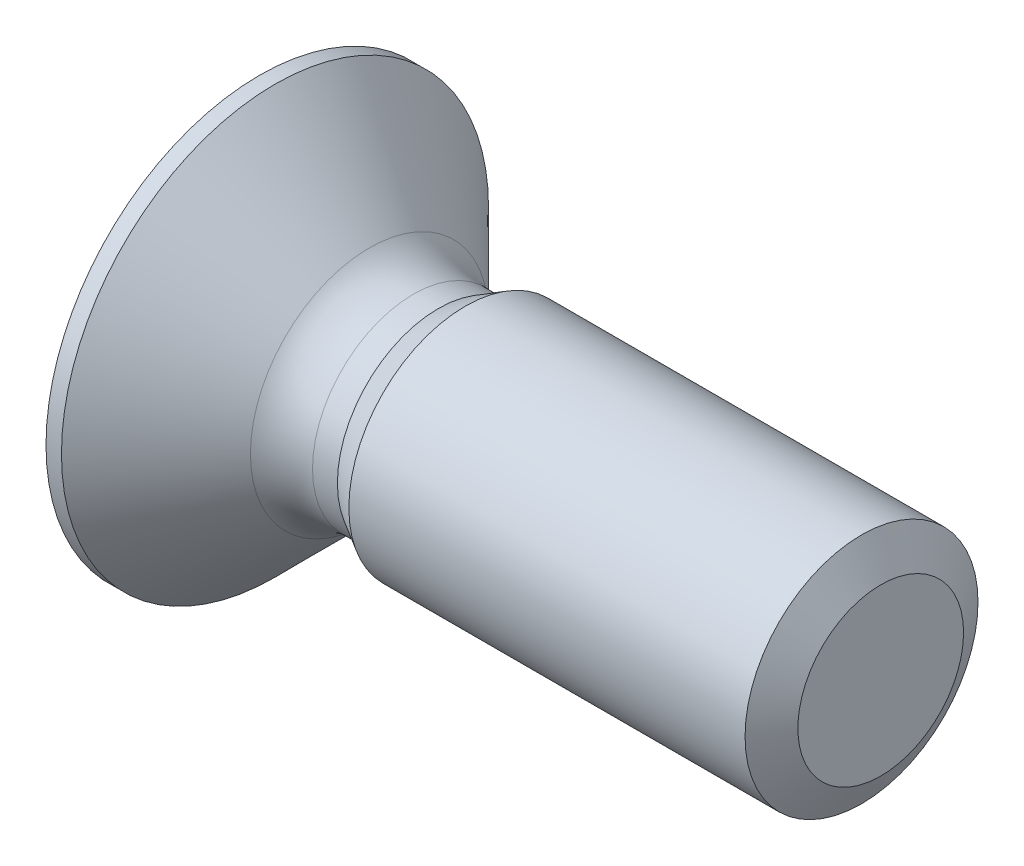
SolidWorks part; units mm, degrees
revolve "基体-旋转" add sketch "草图1" angle 360 about L0
sketch "草图1" plane through (0, 0, 0) normal (0, 0, 1) x (1, 0, 0)
  line L0 (0, 0) -> (4.4175, 0) construction
  line L1 (0, 0) -> (0, 2.75)
  line L2 (0, 2.75) -> (0.199, 2.75)
  line L3 (0.199, 2.75) -> (1.4157, 1.5333)
  line L4 (1.9814, 1.299) -> (2.3019, 1.299)
  line L5 (2.3019, 1.299) -> (2.65, 1.5)
  line L6 (2.65, 1.5) -> (8, 1.5)
  line L7 (8, 1.5) -> (8, 0)
  line L8 (0, 0) -> (8, 0)
  arc A0 (1.9814, 1.299) -> (1.4157, 1.5333) centre (1.9814, 2.099) cw
  point P12 (1.65, 1.299)
  dimension "D2" = 0.8
  dimension "D1" = 2.598
  dimension "d" = 3
  dimension "dk" = 5.5
  dimension "k" = 1.65
  dimension "D5" = 45
  dimension "a" = 1
  dimension "l" = 8
  dimension "D8" = 30
cosmetic thread "装饰螺纹线2" parameters "D1"=5.35, "D2"=2.5
material "AISI 304"
ref_plane "前视" through (0, 0, 0) normal (0, 0, 1) x (1, 0, 0)
ref_plane "上视" through (0, 0, 0) normal (0, 1, 0) x (1, 0, 0)
ref_plane "右视" through (0, 0, 0) normal (1, 0, 0) x (0, 0, -1)
sketch "尺寸草图" plane through (0, 0, 0) normal (0, 0, 1) x (1, 0, 0)
  line L0 (0, 0) -> (8, 0)
  point P3 (1.65, 0)
  point P4 (1, 0)
  point P5 (3, 0)
  point P6 (5.5, 0)
  point P7 (4.8, 0)
  point P8 (3.5943, 0)
  point P9 (7.2, 0)
  point P10 (5.9, 0)
  point P11 (7.5, 0)
  dimension "d" = 3
  dimension "dk" = 5.5
  dimension "k" = 1.65
  dimension "a" = 1
  dimension "l" = 8
  dimension "r" = 0.8
  dimension "m" = 3.2
  dimension "h" = 2.1
  dimension "p" = 0.5
sketch "草图2" plane through (0, 0, 0) normal (0, 0, 1) x (1, 0, 0)
  line L0 (7.7527, 1.5) -> (8.2527, 1.5)
  line L1 (8.2527, 1.5) -> (8, 1.067)
  line L2 (8, 1.067) -> (7.7527, 1.5)
  line L3 (8, -1.5) -> (8, 1.5) construction
  line L6 (0, 0) -> (-0.4315, 0) construction
  dimension "D1" = 0.5
  dimension "D2" = 0.433
  dimension "D3" = 1.5
  dimension "D4" = 60
revolve "切除-旋转1" cut sketch "草图2" angle 360 about L6
pattern_linear "阵列(线性)1" [suppressed] count 11 spacing 0.5 along (1, 0, 0)
sketch "草图3" plane through (0, 0, 0) normal (-1, 0, 0) x (0, 0, 1)
  line L0 (0, 0) -> (1.6329, 0) construction
  line L1 (0, 0) -> (0, 0.8499) construction
  line L2 (-1.6, 0.25) -> (1.6, 0.25)
  line L3 (-1.6, 0.25) -> (-1.6, -0.25)
  line L4 (-1.6, -0.25) -> (1.6, -0.25)
  line L5 (1.6, 0.25) -> (1.6, -0.25)
  dimension "m" = 3.2
  dimension "D1" = 0.5
ref_plane "基准面1" through (2.1, 0, 0) normal (-1, 0, 0) x (0, 0, 1)
sketch "草图4" plane through (2.1, 0, 0) normal (-1, 0, 0) x (0, 0, 1)
  point P0 (0, 0)
loft "切除-放样1" cut profiles "草图3", "草图4"
pattern_circular "阵列(圆周)1" count 2 every 90 about axis through (0, 0, 0) along (1, 0, 0) of "切除-放样1"
equation "\"l@草图1\" = \"l@尺寸草图\""
equation "\"k@草图1\" = \"k@尺寸草图\""
equation "\"a@草图1\" = \"a@尺寸草图\""
equation "\"d@草图1\" = \"d@尺寸草图\""
equation "\"dk@草图1\" = \"dk@尺寸草图\""
equation "\"D2@草图1\" = \"r@尺寸草图\""
equation "\"m@草图3\" = \"m@尺寸草图\""
equation "\"h@基准面1\" = \"h@尺寸草图\""
equation "\"D3@阵列(线性)1\" = \"p@尺寸草图\""
equation "\"D3@草图2\" = \"d@草图1\" / 2"
equation "\"D1@装饰螺纹线2\" = \"l@草图1\" - \"k@草图1\" - \"a@草图1\""
equation "\"D2@装饰螺纹线2\" = \"d@尺寸草图\"- \"p@尺寸草图\""
equation "\"D1@阵列(线性)1\" = (  \"l@草图1\" - \"k@草图1\" - \"a@草图1\" )  / \"p@尺寸草图\""
equation "\"D1@草图3\" = \"p@尺寸草图\""
equation "\"D1@草图1\" = \"d@尺寸草图\"*0.866"
equation "\"D2@草图2\" = \"p@尺寸草图\"*0.866"
equation "\"D1@草图2\" = \"p@尺寸草图\""
